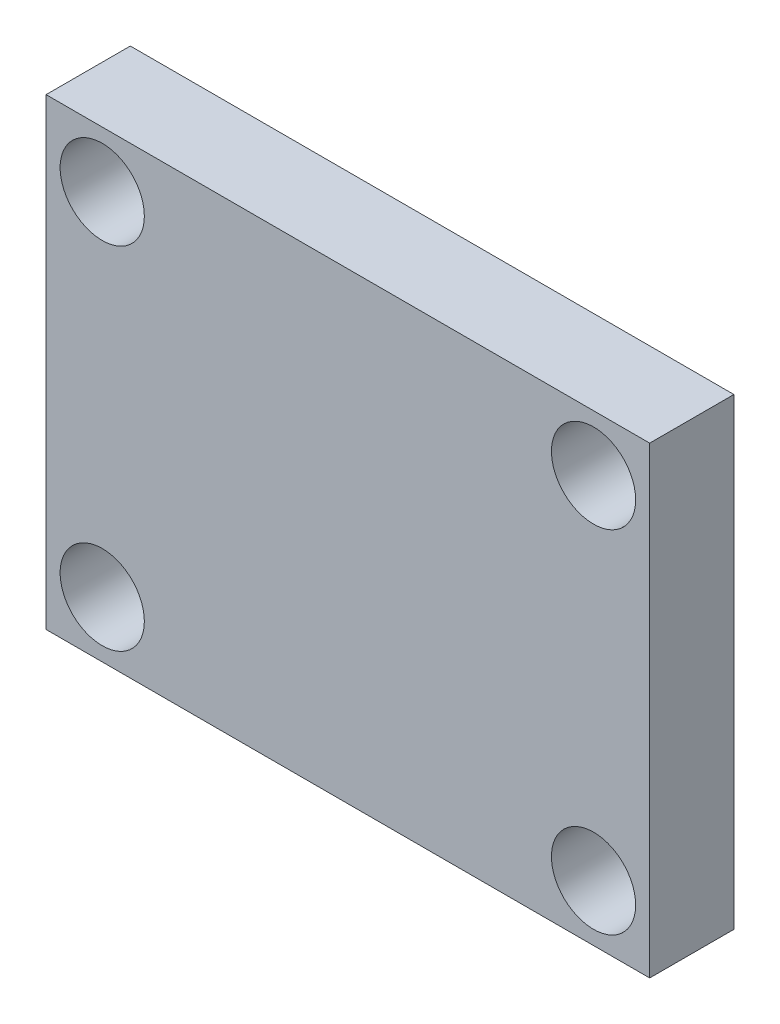
SolidWorks part; units mm, degrees
ref_plane "Front Plane" through (0, 0, 0) normal (0, 0, 1) x (1, 0, 0)
ref_plane "Top Plane" through (0, 0, 0) normal (0, 1, 0) x (1, 0, 0)
ref_plane "Right Plane" through (0, 0, 0) normal (1, 0, 0) x (0, 0, -1)
sketch "Sketch1" plane through (0, 0, 0) normal (0, 0, 1) x (1, 0, 0)
  line L1 (-10.75, -8.25) -> (10.75, -8.25)
  line L2 (-10.75, -8.25) -> (-10.75, 8.25)
  line L3 (-10.75, 8.25) -> (10.75, 8.25)
  line L4 (10.75, -8.25) -> (10.75, 8.25)
  line L5 (-10.75, -8.25) -> (10.75, 8.25) construction
  line L6 (-10.75, 8.25) -> (10.75, -8.25) construction
  line L7 (-8.75, -6.25) -> (8.75, -6.25) construction
  line L8 (-8.75, -6.25) -> (-8.75, 6.25) construction
  line L9 (-8.75, 6.25) -> (8.75, 6.25) construction
  line L10 (8.75, -6.25) -> (8.75, 6.25) construction
  line L11 (-8.75, -6.25) -> (8.75, 6.25) construction
  line L12 (-8.75, 6.25) -> (8.75, -6.25) construction
  circle A0 centre (-8.75, 6.25) radius 1.5
  circle A1 centre (8.75, 6.25) radius 1.5
  circle A2 centre (8.75, -6.25) radius 1.5
  circle A3 centre (-8.75, -6.25) radius 1.5
  point P0 (0, 0)
  point P6 (0, 0)
  dimension "D3" = 3
  dimension "D1" = 21.5
  dimension "D2" = 16.5
  dimension "D4" = 2
  dimension "D5" = 2
extrude "Boss-Extrude1" add sketch "Sketch1" along normal blind 3
